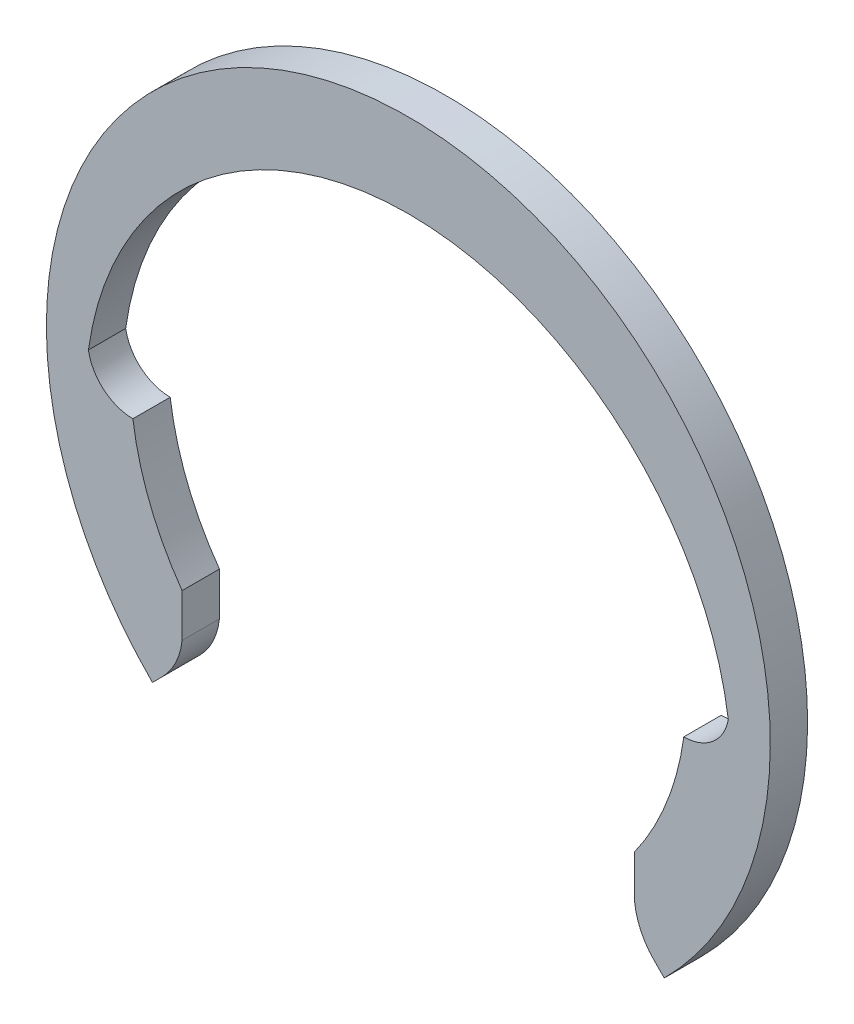
SolidWorks part; units mm, degrees
ref_plane "Front" through (0, 0, 0) normal (0, 0, 1) x (1, 0, 0)
ref_plane "Top" through (0, 0, 0) normal (0, 1, 0) x (1, 0, 0)
ref_plane "Right" through (0, 0, 0) normal (1, 0, 0) x (0, 0, -1)
sketch "Layout" plane through (0, 0, 0) normal (0, 0, 1) x (1, 0, 0)
  line L0 (0, 9.7) -> (0, -9.7) construction
  line L1 (-7.45, 0) -> (-9.7, 0) construction
  line L2 (-9.7, 0) -> (-10.7, 0) construction
  line L3 (-7.45, 0) -> (7.45, 0) construction
  line L4 (-6.0634, -6.0634) -> (-6.0634, -4.3286) construction
  line L5 (-7.3826, -1) -> (7.3826, -1) construction
  line L6 (-7.45, 0) -> (-7.45, -1) construction
  line L7 (0, 0) -> (-5.2679, -5.2679) construction
  line L8 (-5.2679, -5.2679) -> (-6.8589, -6.8589) construction
  circle A0 centre (0, 0) radius 9.7 construction
  circle A1 centre (0, 0) radius 7.45 construction
  arc A2 (0, 7.45) -> (-8.575, 0) centre (0, -1.2099) ccw construction
  circle A3 centre (0, 0) radius 9.95 construction
  arc A4 (-8.575, 0) -> (-7.3826, -1) centre (-7.3826, 0.2109) ccw construction
  dimension "D1" = 45
  dimension "RingOD" = 19.4
  dimension "D3" = 14.9
  dimension "Clear Dia" = 19.9
  dimension "Cad E" = 2.25
  dimension "thickness" = 1
sketch "Sketch2" plane through (0, 0, 0) normal (0, 0, 1) x (1, 0, 0)
  line L0 (-6.0634, -6.0634) -> (-6.0634, -5.4852) construction
  line L1 (-6.0634, -5.4852) -> (-6.0634, -4.9069)
  line L2 (-6.0634, -4.9069) -> (-6.0634, -4.3286)
  line L4 (0, 9.7) -> (0, -9.7) construction
  line L5 (-6.0634, -6.0634) -> (-6.3286, -6.3286) construction
  line L6 (0, 9.7) -> (0, 7.45) construction
  line L7 (-6.3286, -6.3286) -> (-6.5938, -6.5938) construction
  line L8 (-6.5938, -6.5938) -> (-6.8589, -6.8589)
  line L9 (-5.2679, -5.2679) -> (-6.8589, -6.8589) construction
  line L10 (6.0634, -4.9069) -> (6.0634, -4.3286)
  line L11 (6.0634, -5.4852) -> (6.0634, -4.9069)
  line L12 (6.5938, -6.5938) -> (6.8589, -6.8589)
  circle A0 centre (0, 0) radius 9.7 construction
  arc A1 (0, 7.45) -> (-8.575, 0) centre (0, -1.2099) ccw construction
  arc A2 (-8.575, 0) -> (-7.3826, -1) centre (-7.3826, 0.2109) ccw construction
  circle A3 centre (0, 0) radius 7.45 construction
  arc A4 (6.8589, -6.8589) -> (-6.8589, -6.8589) centre (0, 0) ccw
  arc A5 (8.575, 0) -> (-8.575, 0) centre (0, -1.2099) ccw
  arc A6 (-8.575, 0) -> (-7.3826, -1) centre (-7.3826, 0.2109) ccw
  arc A7 (-7.3826, -1) -> (-6.0634, -4.3286) centre (0, 0) ccw
  arc A8 (-6.0634, -5.4852) -> (-6.5938, -6.5938) centre (-7.8996, -5.2879) cw
  arc A9 (6.0634, -5.4852) -> (6.5938, -6.5938) centre (7.8996, -5.2879) ccw
  arc A10 (7.3826, -1) -> (6.0634, -4.3286) centre (0, 0) cw
  arc A11 (8.575, 0) -> (7.3826, -1) centre (7.3826, 0.2109) cw
extrude "Boss-Extrude1" add sketch "Sketch2" along normal blind 1
equation "\"D1@Boss-Extrude1\"=\"thickness@Layout\""
